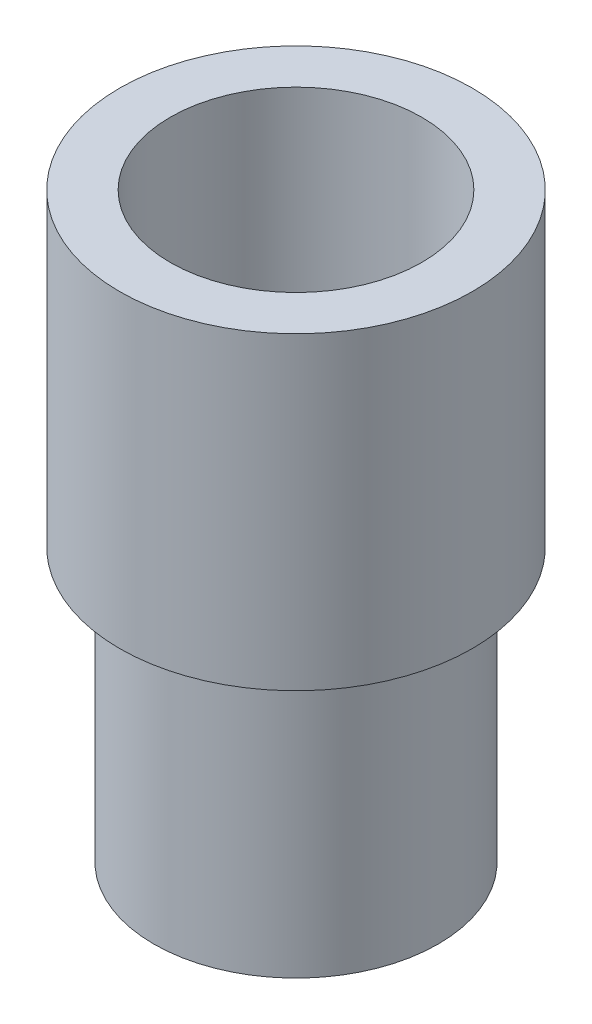
SolidWorks part; units mm, degrees
ref_plane "Front Plane" through (0, 0, 0) normal (0, 0, 1) x (1, 0, 0)
ref_plane "Top Plane" through (0, 0, 0) normal (0, 1, 0) x (1, 0, 0)
ref_plane "Right Plane" through (0, 0, 0) normal (1, 0, 0) x (0, 0, -1)
sketch "Sketch1" plane through (0, 0, 0) normal (0, 0, 1) x (1, 0, 0)
  line L0 (0, 0) -> (0, 65) construction
  line L2 (14.0462, 0) -> (15.875, 0)
  line L3 (14.0462, 0) -> (14.0462, 30.48)
  line L4 (14.0462, 30.48) -> (15.875, 30.48)
  line L5 (15.875, 0) -> (15.875, 30.48)
  line L6 (14.0462, 30.48) -> (19.685, 30.48)
  line L7 (14.0462, 30.48) -> (14.0462, 65)
  line L8 (14.0462, 65) -> (19.685, 65)
  line L9 (19.685, 30.48) -> (19.685, 65)
  line L10 (14.0462, 40.48) -> (0, 40.48)
  line L11 (14.0462, 40.48) -> (14.0462, 30.48)
  line L12 (14.0462, 30.48) -> (0, 30.48)
  line L13 (0, 40.48) -> (0, 30.48)
  dimension "D1" = 65
  dimension "D2" = 31.75
  dimension "D3" = 1.8288
  dimension "D4" = 30.48
  dimension "D5" = 3.81
  dimension "D6" = 10
revolve "Revolve1" add sketch "Sketch1" angle 360 about L0
